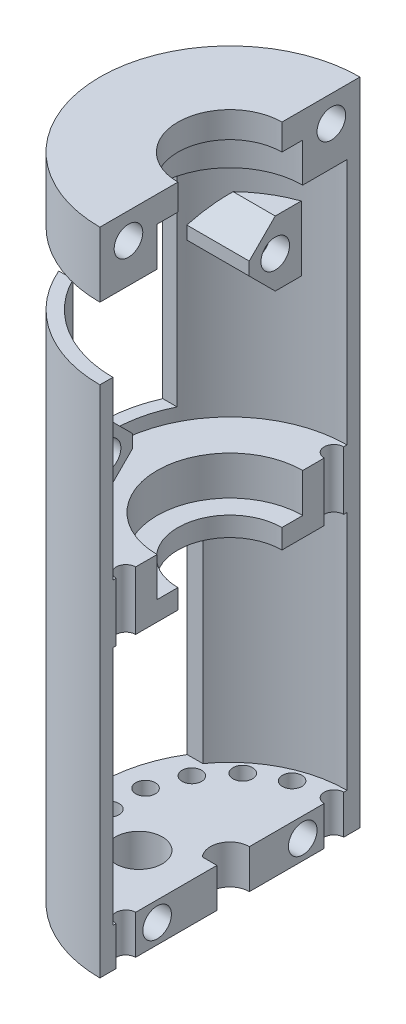
SolidWorks part; units mm, degrees
ref_plane "前视基准面" through (0, 0, 0) normal (0, 0, 1) x (1, 0, 0)
ref_plane "上视基准面" through (0, 0, 0) normal (0, 1, 0) x (1, 0, 0)
ref_plane "右视基准面" through (0, 0, 0) normal (1, 0, 0) x (0, 0, -1)
sketch "草图1" plane through (0, 0, 0) normal (0, 1, 0) x (1, 0, 0)
  line L2 (-1.118, -1) -> (1.118, -1)
  circle A0 centre (0, 0) radius 10
  arc A4 (1.118, -1) -> (-1.118, -1) centre (0, 0) ccw
extrude "凸台-拉伸1" add sketch "草图1" along normal blind 3
sketch "草图2" plane through (0, 3, 0) normal (0, 1, 0) x (1, 0, 0)
  line L1 (0, 0) -> (0, 8) construction
  circle A18 centre (0, 8) radius 0.75
  circle A19 centre (2.7362, 7.5175) radius 0.75
  circle A20 centre (5.1423, 6.1284) radius 0.75
  circle A21 centre (6.9282, 4) radius 0.75
  circle A22 centre (7.8785, 1.3892) radius 0.75
  circle A23 centre (7.8785, -1.3892) radius 0.75
  circle A24 centre (6.9282, -4) radius 0.75
  circle A25 centre (5.1423, -6.1284) radius 0.75
  circle A26 centre (2.7362, -7.5175) radius 0.75
  circle A27 centre (0, -8) radius 0.75
  circle A28 centre (-2.7362, -7.5175) radius 0.75
  circle A29 centre (-5.1423, -6.1284) radius 0.75
  circle A30 centre (-6.9282, -4) radius 0.75
  circle A31 centre (-7.8785, -1.3892) radius 0.75
  circle A32 centre (-7.8785, 1.3892) radius 0.75
  circle A33 centre (-6.9282, 4) radius 0.75
  circle A34 centre (-5.1423, 6.1284) radius 0.75
  circle A35 centre (-2.7362, 7.5175) radius 0.75
  point P41 (0, 0)
  point P42 (0, 0)
extrude "切除-拉伸1" cut sketch "草图2" against normal up to next
sketch "草图3" plane through (0, 3, 0) normal (0, 1, 0) x (1, 0, 0)
  circle A0 centre (0, 0) radius 10
  circle A1 centre (0, 0) radius 9
extrude "凸台-拉伸2" add sketch "草图3" along normal blind 47
sketch "草图4" plane through (0, 50, 0) normal (0, 1, 0) x (1, 0, 0)
  line L0 (0, -10) -> (0, 10)
  circle A0 centre (0, 0) radius 10 construction
  arc A1 (0, -10) -> (0, 10) centre (0, 0) ccw
extrude "切除-拉伸2" cut sketch "草图4" against normal blind 50
ref_plane "基准面4" through (0, 29, 0) normal (0, 1, 0) x (1, 0, 0)
sketch "草图5" plane through (0, 29, 0) normal (0, 1, 0) x (1, 0, 0)
  line L2 (-3, -8.4853) -> (-3, -4.4853)
  line L3 (-3, -4.4853) -> (-7.8027, -4.4853)
  circle A0 centre (0, 0) radius 9 construction
  arc A1 (-3, -8.4853) -> (-7.8027, -4.4853) centre (0, 0) cw
extrude "凸台-拉伸3" add sketch "草图5" along normal blind 5
sketch "草图6" plane through (-3, 0, 0) normal (1, 0, 0) x (0, 0, -1)
  circle A0 centre (-6.4853, 31.5) radius 1.1
extrude "切除-拉伸3" cut sketch "草图6" against normal blind 1.5
ref_plane "基准面5" through (0, 41, 0) normal (0, 1, 0) x (1, 0, 0)
sketch "草图7" plane through (0, 41, 0) normal (0, 1, 0) x (1, 0, 0)
  line L2 (-3, 8.4853) -> (-3, 4.4853)
  line L3 (-3, 4.4853) -> (-7.8027, 4.4853)
  circle A0 centre (0, 0) radius 9 construction
  arc A1 (-3, 8.4853) -> (-7.8027, 4.4853) centre (0, 0) ccw
extrude "凸台-拉伸4" add sketch "草图7" against normal blind 5
sketch "草图8" plane through (-3, 0, 0) normal (1, 0, 0) x (0, 0, -1)
  circle A0 centre (6.4853, 38.5) radius 1.1
extrude "切除-拉伸4" cut sketch "草图8" against normal blind 1.5
sketch "草图9" plane through (0, 0, 0) normal (0, -1, 0) x (1, 0, 0)
  line L1 (0, 9) -> (0, 5.6)
  line L2 (0, -5.6) -> (0, -9)
  arc A3 (0, 9) -> (0, -9) centre (0, 0) ccw
  arc A4 (0, 5.6) -> (0, -5.6) centre (0, 0) ccw
extrude "凸台-拉伸5" add sketch "草图9" against normal blind 3 from offset 23 offset against normal yes
sketch "草图10" plane through (0, 23, 0) normal (0, -1, 0) x (1, 0, 0)
  line L1 (0, 9) -> (0, 4)
  line L2 (0, -4) -> (0, -9)
  arc A2 (0, 9) -> (0, -9) centre (0, 0) ccw
  arc A3 (0, 4) -> (0, -4) centre (0, 0) ccw
extrude "凸台-拉伸6" add sketch "草图10" along normal blind 1.5
sketch "草图11" plane through (0, 50, 0) normal (0, 1, 0) x (1, 0, 0)
  line L2 (0, -9) -> (0, -4)
  line L3 (0, 4) -> (0, 9)
  arc A2 (0, -9) -> (0, 9) centre (0, 0) cw
  arc A3 (0, -4) -> (0, 4) centre (0, 0) cw
extrude "凸台-拉伸7" add sketch "草图11" against normal blind 2
sketch "草图12" plane through (0, 48, 0) normal (0, -1, 0) x (1, 0, 0)
  line L1 (0, 9) -> (0, 5.6)
  line L2 (0, -5.6) -> (0, -9)
  arc A2 (0, 9) -> (0, -9) centre (0, 0) ccw
  arc A3 (0, 5.6) -> (0, -5.6) centre (0, 0) ccw
extrude "凸台-拉伸8" add sketch "草图12" along normal blind 3
sketch "草图13" plane through (0, 26, 0) normal (0, 1, 0) x (1, 0, 0)
  circle A0 centre (0, 0) radius 8 construction
  circle A1 centre (0, 8) radius 0.75
  circle A2 centre (0, -8) radius 0.75
extrude "切除-拉伸5" cut sketch "草图13" against normal up to next
sketch "草图14" plane through (0, 0, 0) normal (1, 0, 0) x (0, 0, -1)
  line L0 (-9, 21.5) -> (9, 21.5) construction
  line L2 (5.2362, 21.5) -> (5.2362, 3)
  line L5 (7.25, 21.5) -> (4, 21.5) construction
  line L8 (5.2362, 21.5) -> (-5.2639, 21.5)
  line L9 (-5.2639, 21.5) -> (-5.2639, 3)
  line L10 (-5.2639, 3) -> (5.2362, 3)
  point P0 (-1.8125, 12.75)
extrude "切除-拉伸6" cut sketch "草图14" against normal up to next
sketch "草图15" plane through (0, 0, 0) normal (1, 0, 0) x (0, 0, -1)
  line L0 (-3.6373, 45) -> (-10, 45)
  line L1 (4, 45) -> (-3.6373, 45)
  line L2 (4, 45) -> (4, 27)
  line L3 (4, 27) -> (-4, 27)
  line L5 (4, 45) -> (-4, 27) construction
  line L6 (4, 27) -> (-3.6373, 45) construction
  line L7 (-10, 0) -> (-10, 50) construction
  line L8 (-10, 45) -> (-10, 39.5)
  line L11 (-10, 39.5) -> (-4, 39.5)
  line L12 (-4, 39.5) -> (-4, 27)
  point P0 (0.0928, 36.2088)
extrude "切除-拉伸7" cut sketch "草图15" against normal up to next
sketch "草图16" plane through (0, 0, 0) normal (1, 0, 0) x (0, 0, -1)
  circle A0 centre (-7.8, 48) radius 1.1
  circle A1 centre (7.8, 48) radius 1.1
  circle A2 centre (-5.6, 1.5) radius 1.1
  circle A3 centre (5.6, 1.5) radius 1.1
extrude "切除-拉伸8" cut sketch "草图16" against normal blind 3
chamfer "倒角1" distance 2 angle 45 4 edges at (-5.4014, 36, -4.4853) (-5.4014, 41, -4.4853) (-5.4014, 29, 4.4853) (-5.4014, 34, 4.4853)
sketch "Sketch1" plane through (0, 3, 0) normal (0, 1, 0) x (1, 0, 0)
  circle A0 centre (-4, -3) radius 1.8
extrude "Cut-Extrude1" cut sketch "Sketch1" against normal up to next
